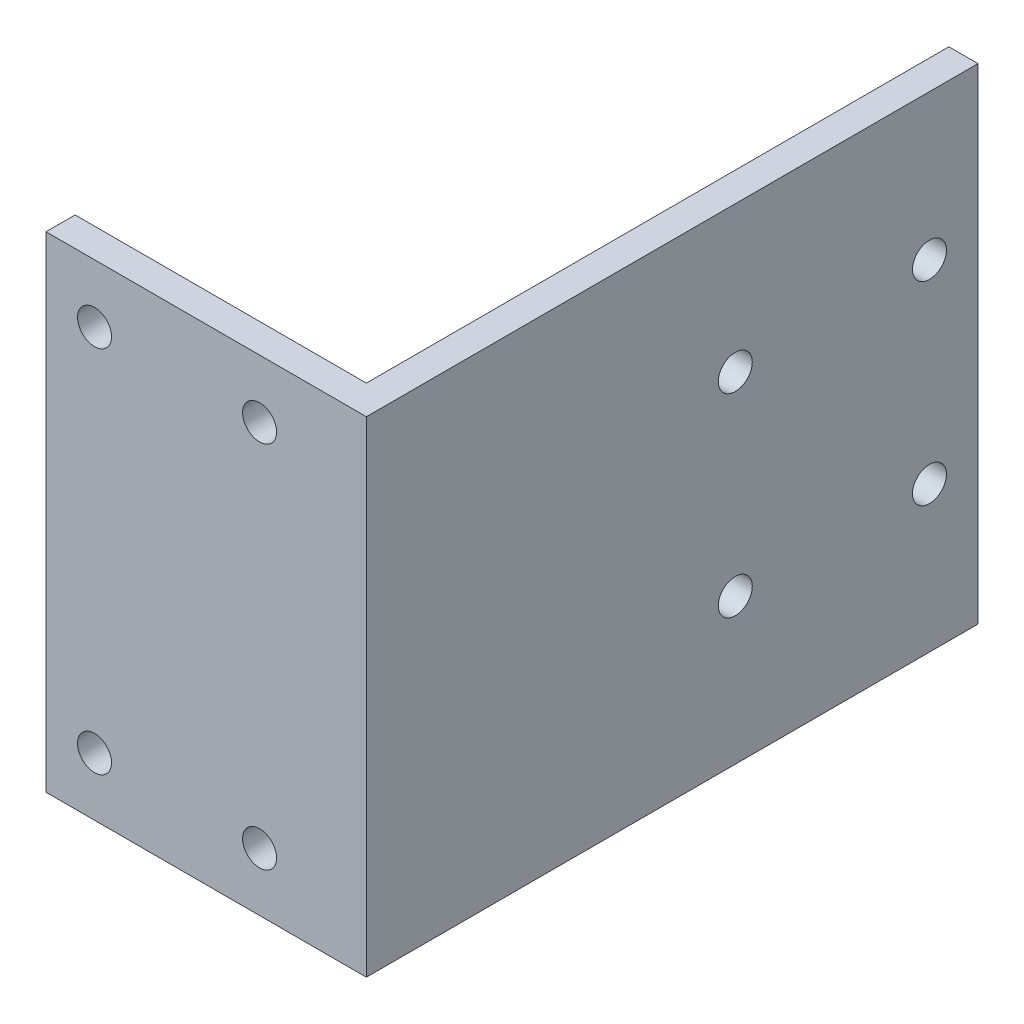
SolidWorks part; units mm, degrees
ref_plane "前视基准面" through (0, 0, 0) normal (0, 0, 1) x (1, 0, 0)
ref_plane "上视基准面" through (0, 0, 0) normal (0, 1, 0) x (1, 0, 0)
ref_plane "右视基准面" through (0, 0, 0) normal (1, 0, 0) x (0, 0, -1)
sketch "草图1" plane through (0, 0, 0) normal (0, 1, 0) x (1, 0, 0)
  line L0 (0, 0) -> (30, 0)
  line L1 (30, 0) -> (30, 60)
  line L2 (0, -3) -> (33, -3)
  line L3 (33, -3) -> (33, 60)
  line L4 (0, -3) -> (0, 0)
  line L5 (30, 60) -> (33, 60)
  dimension "D2" = 30
  dimension "D3" = 60
  dimension "D1" = 3
extrude "凸台-拉伸1" add sketch "草图1" along normal blind 50
sketch "草图2" plane through (0, 0, 0) normal (0, 0, -1) x (-1, 0, 0)
  line L1 (-30, 0) -> (0, 0) construction
  line L2 (-30, 50) -> (-30, 0) construction
  circle A0 centre (-22, 6) radius 1.75
  circle A1 centre (-22, 44) radius 1.75
  circle A2 centre (-5, 44) radius 1.75
  circle A3 centre (-5, 6) radius 1.75
  dimension "D1" = 3.5
  dimension "D2" = 6
  dimension "D3" = 38
  dimension "D4" = 8
  dimension "D5" = 17
  dimension "D6" = 38
extrude "切除-拉伸1" cut sketch "草图2" against normal through all
sketch "草图3" plane through (33, 0, 0) normal (1, 0, 0) x (0, 0, -1)
  line L0 (60, 50) -> (60, 0) construction
  line L1 (-3, 50) -> (60, 50) construction
  circle A0 centre (55, 35) radius 1.75
  circle A1 centre (55, 15) radius 1.75
  circle A2 centre (35, 35) radius 1.75
  circle A3 centre (35, 15) radius 1.75
  dimension "D1" = 3.5
  dimension "D2" = 5
  dimension "D3" = 15
  dimension "D4" = 20
  dimension "D5" = 20
  dimension "D6" = 20
extrude "切除-拉伸2" cut sketch "草图3" against normal up to next
